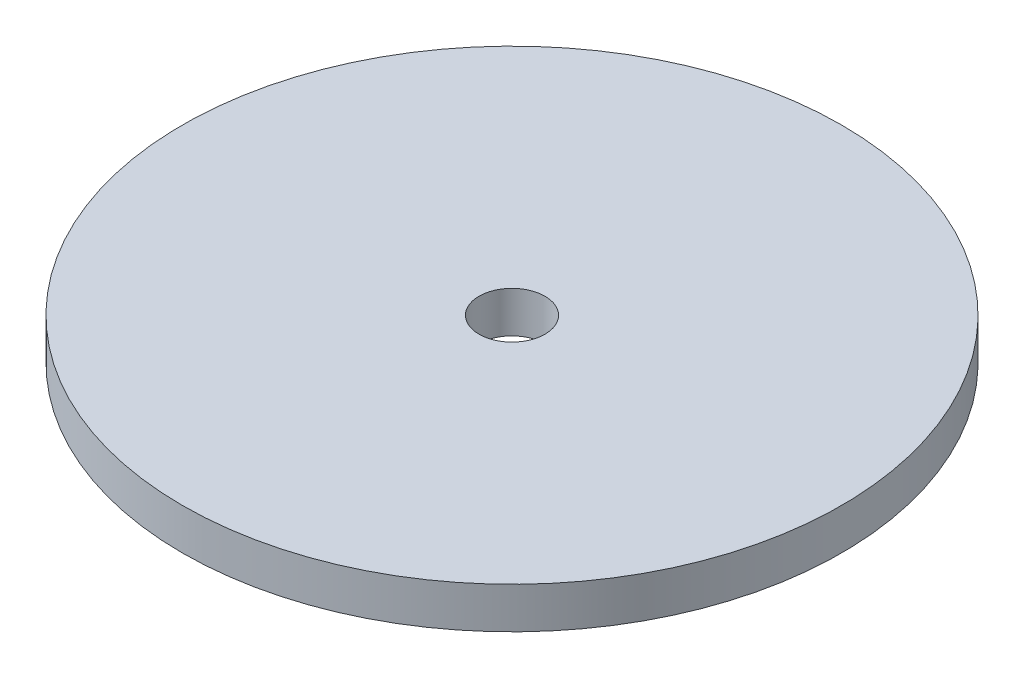
SolidWorks part; units mm, degrees
ref_plane "Front Plane" through (0, 0, 0) normal (0, 0, 1) x (1, 0, 0)
ref_plane "Top Plane" through (0, 0, 0) normal (0, 1, 0) x (1, 0, 0)
ref_plane "Right Plane" through (0, 0, 0) normal (1, 0, 0) x (0, 0, -1)
sketch "Sketch1" plane through (0, 0, 0) normal (0, 1, 0) x (1, 0, 0)
  circle A0 centre (0, 0) radius 25.4
  dimension "D1" = 50.8
extrude "Boss-Extrude1" add sketch "Sketch1" along normal blind 3.175
sketch "Sketch2" plane through (0, 3.175, 0) normal (0, 1, 0) x (1, 0, 0)
  circle A0 centre (0, 0) radius 2.54
  dimension "D1" = 5.08
extrude "Cut-Extrude1" cut sketch "Sketch2" against normal blind 3.175
